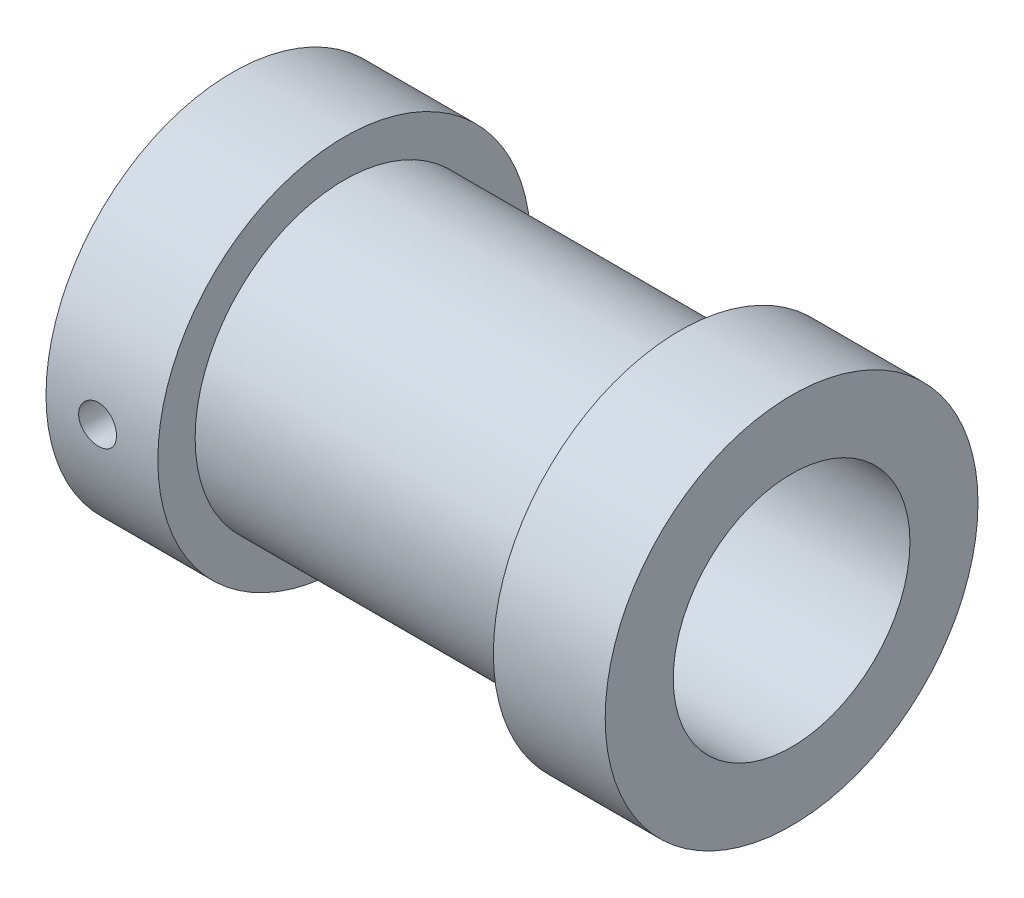
SolidWorks part; units mm, degrees
ref_plane "Front Plane" through (0, 0, 0) normal (0, 0, 1) x (1, 0, 0)
ref_plane "Top Plane" through (0, 0, 0) normal (0, 1, 0) x (1, 0, 0)
ref_plane "Right Plane" through (0, 0, 0) normal (1, 0, 0) x (0, 0, -1)
sketch "Sketch1" plane through (0, 0, 0) normal (1, 0, 0) x (0, 0, -1)
  circle A0 centre (0, 0) radius 5
  circle A1 centre (0, 0) radius 3.175
  dimension "D1" = 6.35
  dimension "D2" = 10
extrude "Boss-Extrude1" add sketch "Sketch1" along normal blind 15
sketch "Sketch2" plane through (0, 0, 0) normal (0, 0, 1) x (1, 0, 0)
  line L0 (15, 5) -> (0, 5) construction
  line L1 (3, 5) -> (12, 5)
  line L2 (3, 5) -> (3, 4)
  line L3 (3, 4) -> (12, 4)
  line L4 (12, 5) -> (12, 4)
  line L5 (0, 5) -> (0, -5) construction
  line L6 (15, -5) -> (15, 5) construction
  dimension "D1" = 3
  dimension "D2" = 3
  dimension "D3" = 1
ref_axis "Axis1" through (15, 0, 0) along (-1, 0, 0)
revolve "Cut-Revolve1" cut sketch "Sketch2" angle 360 about axis through (15, 0, 0) along (-1, 0, 0)
hole_wizard "#60 (0.04) Diameter Hole1" positions "Sketch4" profile "Sketch3" hole size "#60" standard "ANSI Inch"
sketch "Sketch4" plane through (0, 0, 0) normal (0, 0, 1) x (1, 0, 0)
  line L0 (15, 0) -> (0, 0) construction
  point P0 (1.3829, 0)
sketch "Sketch3" plane through (1.3829, 0, 0) normal (1, 0, 0) x (0, 1, 0)
  line L0 (0, 0) -> (0, 25.7052)
  line L1 (0, 25.7052) -> (0.508, 25.4)
  line L2 (0.508, 25.4) -> (0.508, 0)
  line L5 (0.508, 0) -> (0, 0)
  line L10 (0, 25.7052) -> (-0.508, 25.4) construction
  line L11 (0, -6.35) -> (0, 107.95) construction
  dimension "Hole Dia." = 1.016
  dimension "Hole Depth" = 25.4
  dimension "Drill Angle" = 118
ref_plane "Plane1" through (0, 0, -5.08) normal (0, 0, 1) x (1, 0, 0)
